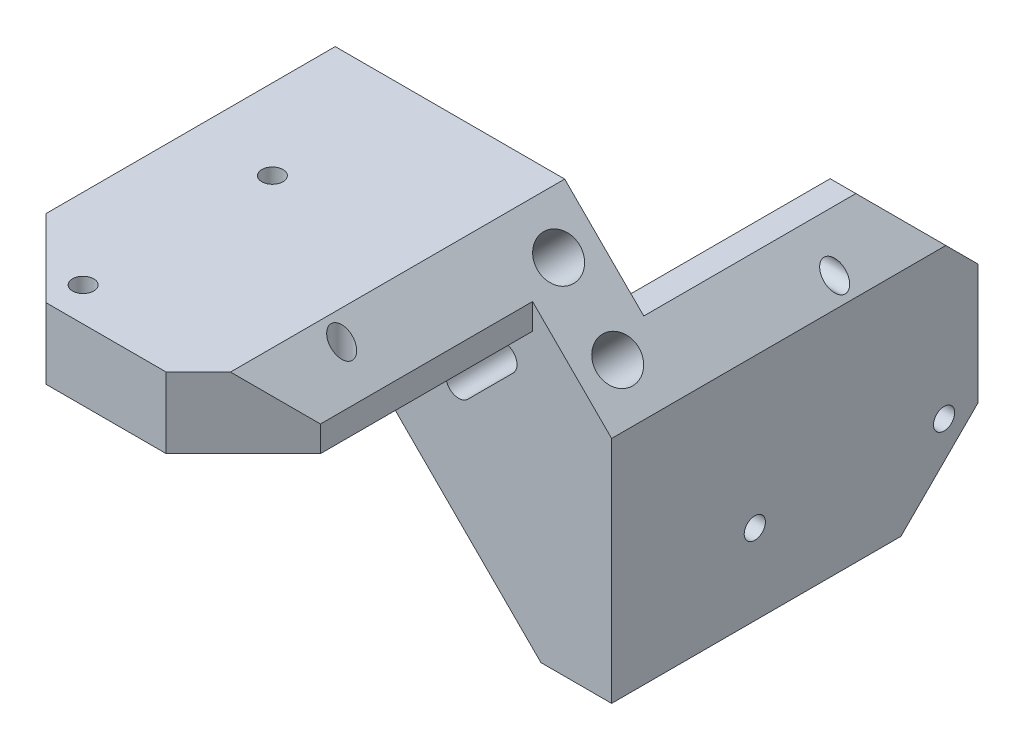
SolidWorks part; units mm, degrees
material "6061"
ref_plane "前视" through (0, 0, 0) normal (0, 0, 1) x (1, 0, 0)
ref_plane "上视" through (0, 0, 0) normal (0, 1, 0) x (1, 0, 0)
ref_plane "右视" through (0, 0, 0) normal (1, 0, 0) x (0, 0, -1)
sketch "草图1" plane through (0, 0, 0) normal (0, 0, 1) x (1, 0, 0)
  line L1 (-27.5, -27.5) -> (27.5, -27.5)
  line L2 (-27.5, -27.5) -> (-27.5, 27.5)
  line L3 (-27.5, 27.5) -> (27.5, 27.5)
  line L4 (27.5, -27.5) -> (27.5, 27.5)
  line L5 (-27.5, -27.5) -> (27.5, 27.5) construction
  line L6 (-27.5, 27.5) -> (27.5, -27.5) construction
  point P0 (0, 0)
  dimension "D1" = 55
extrude "凸台-拉伸1" add sketch "草图1" along normal mid plane 102
sketch "草图2" plane through (0, 0, 51) normal (0, 0, 1) x (1, 0, 0)
  line L1 (-27.5, -27.5) -> (16.5, -27.5)
  line L2 (-27.5, -27.5) -> (-27.5, 16.5)
  line L3 (-27.5, 27.5) -> (-27.5, -27.5) construction
  line L5 (-27.5, 16.5) -> (16.5, -27.5)
  line L6 (-27.5, -27.5) -> (27.5, -27.5) construction
  line L7 (27.5, -27.5) -> (27.5, 27.5) construction
  dimension "D1" = 11
extrude "切除-拉伸1" cut sketch "草图2" against normal through all
chamfer "倒角1" distance 19.3 angle 45 1 edges at (27.5, 27.5, 0)
sketch "草图11" plane through (27.5, 0, 0) normal (1, 0, 0) x (0, 1, 0)
  line L1 (27.5, -51) -> (-27.5, -51)
  line L2 (27.5, -51) -> (27.5, -6)
  line L3 (27.5, -6) -> (-27.5, -6)
  line L4 (-27.5, -51) -> (-27.5, -6)
  line L5 (-27.5, 0) -> (52.6284, 0) construction
  line L7 (-27.5, -51) -> (16.5, -51) construction
  line L9 (-27.5, 51) -> (-27.5, -51) construction
  point P9 (-27.5, -6)
  point P12 (27.5, -6)
  dimension "D1" = 6
extrude "切除-拉伸2" cut sketch "草图11" against normal through all from offset 11 offset against normal yes
sketch "草图12" plane through (0, 27.5, 0) normal (0, -1, 0) x (1, 0, 0)
  line L0 (27.5, 51) -> (27.5, -51) construction
  line L1 (-27.5, 51) -> (27.5, 51)
  line L2 (-27.5, 51) -> (-27.5, 6)
  line L3 (-27.5, 6) -> (27.5, 6)
  line L4 (27.5, 51) -> (27.5, 6)
  line L5 (27.5, 0) -> (60.1478, 0) construction
  line L6 (-27.5, -6) -> (-27.5, 51) construction
  line L7 (16.5, 51) -> (-27.5, 51) construction
extrude "切除-拉伸3" cut sketch "草图12" along normal through all from offset 11
hole_wizard "M4 螺纹孔1" positions "草图10" profile "草图9" tap size "M4" standard "Gb" end condition through all
sketch "草图10" plane through (16.5, -23.3923, -4.1262) normal (-1, 0, 0) x (0, 1, 0)
  line L3 (16.8923, 26.8738) -> (33.8923, 26.8738) construction
  line L4 (16.8923, 26.8738) -> (8.3923, 41.5962) construction
  line L8 (-4.1077, 46.8738) -> (42.5923, 46.8738) construction
  line L9 (-4.1077, 46.8738) -> (-4.1077, 1.8738) construction
  circle A3 centre (16.8923, 26.8738) radius 17 construction
  point P0 (33.8923, 26.8738)
  point P28 (8.3923, 41.5962)
  point P36 (8.3923, 12.1513)
  dimension "D1" = 20
  dimension "D3" = 34
  dimension "D4" = 21
  dimension "D2" = 120
sketch "草图9" plane through (16.5, 10.5, -31) normal (0, 1, 0) x (0, 0, 1)
  line L0 (0, 0) -> (0, 11)
  line L1 (0, 11) -> (1.65, 11)
  line L2 (1.65, 11) -> (1.65, 0)
  line L5 (1.65, 0) -> (0, 0)
  line L11 (0, -6.35) -> (0, 107.95) construction
  dimension "通孔螺纹孔钻头直径" = 3.3
  dimension "通孔螺纹孔钻头深度" = 11
cosmetic thread "孔螺蚊线11" parameters "D1"=6, "D2"=4
cosmetic thread "孔螺蚊线12" parameters "D1"=6, "D2"=4
cosmetic thread "孔螺蚊线19" parameters "D1"=6, "D2"=4
hole_wizard "M4 螺纹孔2" positions "草图14" profile "草图13" tap size "M4" standard "Gb" end condition through all
sketch "草图14" plane through (-3.7764, 16.5, -11.3606) normal (0, -1, 0) x (-1, 0, 0)
  line L0 (2.7236, -42.3606) -> (-14.2764, -42.3606) construction
  line L1 (2.7236, -42.3606) -> (11.2236, -57.083) construction
  line L5 (23.7236, -62.3606) -> (23.7236, -17.3606) construction
  line L7 (-22.9764, -62.3606) -> (23.7236, -62.3606) construction
  circle A0 centre (2.7236, -42.3606) radius 17 construction
  point P0 (-14.2764, -42.3606)
  point P11 (11.2236, -57.083)
  point P21 (11.2236, -27.6381)
  dimension "D2" = 34
  dimension "D3" = 21
  dimension "D4" = 20
  dimension "D1" = 120
sketch "草图13" plane through (10.5, 16.5, 31) normal (1, 0, 0) x (0, 0, -1)
  line L0 (0, 0) -> (0, 11)
  line L1 (0, 11) -> (1.65, 11)
  line L2 (1.65, 11) -> (1.65, 0)
  line L5 (1.65, 0) -> (0, 0)
  line L11 (0, -6.35) -> (0, 107.95) construction
  dimension "通孔螺纹孔钻头直径" = 3.3
  dimension "通孔螺纹孔钻头深度" = 11
cosmetic thread "孔螺蚊线16" parameters "D2"=4
cosmetic thread "孔螺蚊线17" parameters "D2"=4
cosmetic thread "孔螺蚊线18" parameters "D2"=4
hole_wizard "打孔尺寸根据内六角圆柱头螺钉的类型1" positions "草图16" profile "草图15" counterbore size "M6" standard "Gb" end condition through all
sketch "草图16" plane through (-5.5, -5.5, 0) normal (-0.7071, -0.7071, 0) x (-0.7071, 0.7071, 0)
  line L1 (0, 0) -> (6.5, 0) construction
  line L2 (0, 0) -> (0, -9.3381) construction
  point P0 (6.5, 0)
  point P14 (-6.5, 0)
  dimension "D1" = 13
sketch "草图15" plane through (-10.0962, -0.9038, 0) normal (0, 0, 1) x (0.7071, -0.7071, 0)
  line L0 (0, 0) -> (0, 46.669)
  line L1 (0, 46.669) -> (3.3, 46.669)
  line L3 (3.3, 46.669) -> (3.3, 8)
  line L4 (3.3, 8) -> (5.5, 8)
  line L5 (5.5, 8) -> (5.5, 0)
  line L7 (5.5, 0) -> (0, 0)
  line L11 (0, -6.35) -> (0, 107.95) construction
  dimension "通孔孔直径" = 6.6
  dimension "通孔孔深度" = 46.669
  dimension "柱形沉头孔直径" = 11
  dimension "柱形沉头孔深度" = 8
sketch "草图22" plane through (0, 16.5, 0) normal (0, -1, 0) x (1, 0, 0)
  line L0 (16.5, 6) -> (27.5, 6) construction
  line L1 (3.2, 51) -> (15.2, 39)
  line L2 (15.2, 39) -> (15.2, 6)
  line L3 (19.2, 51) -> (-27.5, 51) construction
  line L4 (-27.5, 6) -> (19.2, 6) construction
  line L5 (3.2, 51) -> (19.2, 51)
  line L6 (19.2, 51) -> (19.2, 6)
  line L7 (19.2, 51) -> (19.2, 6) construction
  line L8 (15.2, 6) -> (19.2, 6)
  dimension "D1" = 16
  dimension "D2" = 4
  dimension "D3" = 45
extrude "切除-拉伸5" cut sketch "草图22" against normal through all
sketch "草图23" plane through (16.5, 0, 0) normal (-1, 0, 0) x (0, 0, 1)
  line L0 (-51, 19.2) -> (-51, 3.2)
  line L1 (-51, -27.5) -> (-51, 19.2) construction
  line L2 (-51, 3.2) -> (-39, 15.2)
  line L3 (-6, 19.2) -> (-51, 19.2) construction
  line L4 (-6, 19.2) -> (-51, 19.2)
  line L5 (-39, 15.2) -> (-6, 15.2)
  line L6 (-6, 16.5) -> (-6, -27.5) construction
  line L7 (-6, 15.2) -> (-6, 19.2)
  dimension "D1" = 45
  dimension "D2" = 16
  dimension "D3" = 4
extrude "切除-拉伸6" cut sketch "草图23" against normal through all
chamfer "倒角2" distance 12 angle 45 2 edges at (22, -27.5, -51) (-27.5, 22, 51)
sketch "草图24" plane through (0, 0, -6) normal (0, 0, -1) x (-1, 0, 0)
  line L0 (-3.8191, 13.0115) -> (-13.0115, 3.8191) construction
  line L3 (-13.0115, 3.8191) -> (-8.4153, 8.4153) construction
  line L4 (-8.4153, 8.4153) -> (-3.7208, 3.7208) construction
  line L5 (-3.7079, 3.7079) -> (-10.7789, 10.7789) construction
  line L6 (-5.1221, 2.2937) -> (-12.1931, 9.3647)
  line L7 (-2.2937, 5.1221) -> (-9.3647, 12.1931)
  line L8 (-8.2, 27.5) -> (-20.5, 15.2) construction
  line L12 (-22.4462, 13.2538) -> (-4.753, -4.4393) construction
  line L13 (-13.2538, 22.4462) -> (4.4393, 4.753) construction
  arc A0 (-5.1221, 2.2937) -> (-2.2937, 5.1221) centre (-3.7079, 3.7079) ccw
  arc A1 (-9.3647, 12.1931) -> (-12.1931, 9.3647) centre (-10.7789, 10.7789) ccw
  point P10 (-7.2434, 7.2434)
  dimension "D1" = 4
  dimension "D2" = 10
  dimension "D3" = 10
extrude "切除-拉伸7" cut sketch "草图24" against normal through all
